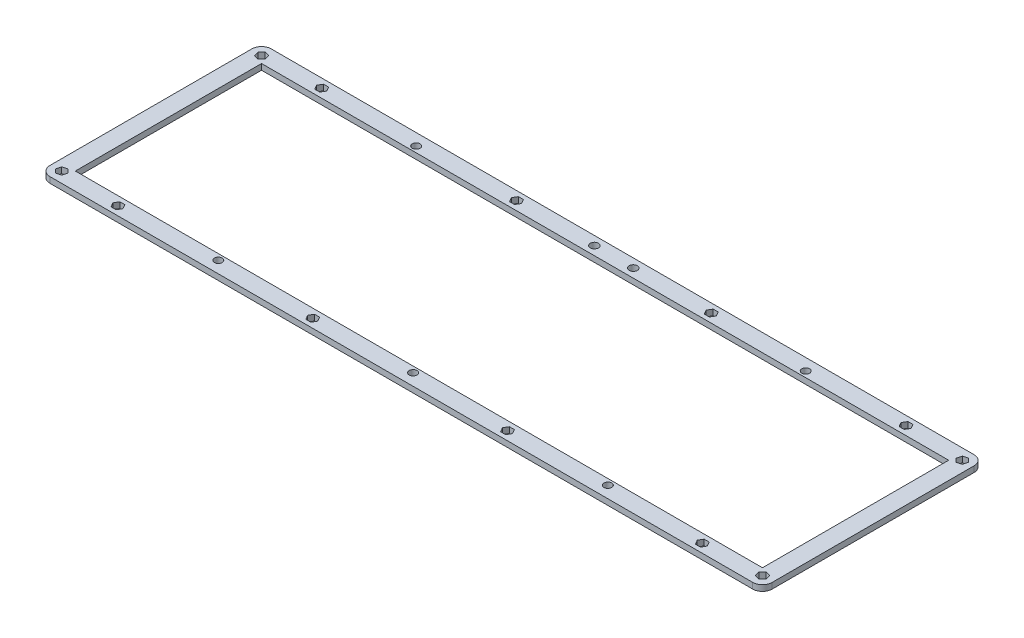
SolidWorks part; units mm, degrees
ref_plane "Front Plane" through (0, 0, 0) normal (0, 0, 1) x (1, 0, 0)
ref_plane "Top Plane" through (0, 0, 0) normal (0, 1, 0) x (1, 0, 0)
ref_plane "Right Plane" through (0, 0, 0) normal (1, 0, 0) x (0, 0, -1)
sketch "Sketch1" plane through (0, 0, 0) normal (0, 1, 0) x (1, 0, 0)
  line L0 (0, 108.6) -> (0, 5)
  line L1 (9, 104.6) -> (9, 9)
  line L2 (365.775, 0) -> (5, 0)
  line L3 (361.775, 9) -> (9, 9)
  line L4 (370.775, 108.6) -> (370.775, 5)
  line L5 (361.775, 104.6) -> (361.775, 9)
  line L6 (365.775, 113.6) -> (5, 113.6)
  line L7 (361.775, 104.6) -> (9, 104.6)
  line L8 (234.0885, 111.35) -> (236.6865, 111.35)
  line L9 (236.6865, 111.35) -> (237.9856, 109.1)
  line L10 (237.9856, 109.1) -> (236.6865, 106.85)
  line L11 (236.6865, 106.85) -> (234.0885, 106.85)
  line L12 (234.0885, 106.85) -> (232.7894, 109.1)
  line L13 (232.7894, 109.1) -> (234.0885, 111.35)
  line L14 (334.0885, 111.35) -> (336.6865, 111.35)
  line L15 (336.6865, 111.35) -> (337.9856, 109.1)
  line L16 (337.9856, 109.1) -> (336.6865, 106.85)
  line L17 (336.6865, 106.85) -> (334.0885, 106.85)
  line L18 (334.0885, 106.85) -> (332.7894, 109.1)
  line L19 (332.7894, 109.1) -> (334.0885, 111.35)
  line L20 (365.9474, 110.6096) -> (367.7846, 108.7724)
  line L21 (367.7846, 108.7724) -> (367.1121, 106.2629)
  line L22 (367.1121, 106.2629) -> (364.6026, 105.5905)
  line L23 (364.6026, 105.5905) -> (362.7655, 107.4276)
  line L24 (362.7655, 107.4276) -> (363.4379, 109.9371)
  line L25 (363.4379, 109.9371) -> (365.9474, 110.6096)
  line L26 (136.6865, 111.35) -> (134.0885, 111.35)
  line L27 (134.0885, 111.35) -> (132.7894, 109.1)
  line L28 (132.7894, 109.1) -> (134.0885, 106.85)
  line L29 (134.0885, 106.85) -> (136.6865, 106.85)
  line L30 (136.6865, 106.85) -> (137.9856, 109.1)
  line L31 (137.9856, 109.1) -> (136.6865, 111.35)
  line L32 (36.6865, 111.35) -> (34.0885, 111.35)
  line L33 (34.0885, 111.35) -> (32.7894, 109.1)
  line L34 (32.7894, 109.1) -> (34.0885, 106.85)
  line L35 (34.0885, 106.85) -> (36.6865, 106.85)
  line L36 (36.6865, 106.85) -> (37.9856, 109.1)
  line L37 (37.9856, 109.1) -> (36.6865, 111.35)
  line L38 (4.8276, 110.6096) -> (2.9905, 108.7724)
  line L39 (2.9905, 108.7724) -> (3.6629, 106.2629)
  line L40 (3.6629, 106.2629) -> (6.1724, 105.5905)
  line L41 (6.1724, 105.5905) -> (8.0096, 107.4276)
  line L42 (8.0096, 107.4276) -> (7.3371, 109.9371)
  line L43 (7.3371, 109.9371) -> (4.8276, 110.6096)
  line L44 (234.0885, 2.25) -> (236.6865, 2.25)
  line L45 (236.6865, 2.25) -> (237.9856, 4.5)
  line L46 (237.9856, 4.5) -> (236.6865, 6.75)
  line L47 (236.6865, 6.75) -> (234.0885, 6.75)
  line L48 (234.0885, 6.75) -> (232.7894, 4.5)
  line L49 (232.7894, 4.5) -> (234.0885, 2.25)
  line L50 (334.0885, 2.25) -> (336.6865, 2.25)
  line L51 (336.6865, 2.25) -> (337.9856, 4.5)
  line L52 (337.9856, 4.5) -> (336.6865, 6.75)
  line L53 (336.6865, 6.75) -> (334.0885, 6.75)
  line L54 (334.0885, 6.75) -> (332.7894, 4.5)
  line L55 (332.7894, 4.5) -> (334.0885, 2.25)
  line L56 (365.9474, 2.9905) -> (367.7846, 4.8276)
  line L57 (367.7846, 4.8276) -> (367.1121, 7.3371)
  line L58 (367.1121, 7.3371) -> (364.6026, 8.0096)
  line L59 (364.6026, 8.0096) -> (362.7655, 6.1724)
  line L60 (362.7655, 6.1724) -> (363.4379, 3.6629)
  line L61 (363.4379, 3.6629) -> (365.9474, 2.9905)
  line L62 (136.6865, 2.25) -> (134.0885, 2.25)
  line L63 (134.0885, 2.25) -> (132.7894, 4.5)
  line L64 (132.7894, 4.5) -> (134.0885, 6.75)
  line L65 (134.0885, 6.75) -> (136.6865, 6.75)
  line L66 (136.6865, 6.75) -> (137.9856, 4.5)
  line L67 (137.9856, 4.5) -> (136.6865, 2.25)
  line L68 (36.6865, 2.25) -> (34.0885, 2.25)
  line L69 (34.0885, 2.25) -> (32.7894, 4.5)
  line L70 (32.7894, 4.5) -> (34.0885, 6.75)
  line L71 (34.0885, 6.75) -> (36.6865, 6.75)
  line L72 (36.6865, 6.75) -> (37.9856, 4.5)
  line L73 (37.9856, 4.5) -> (36.6865, 2.25)
  line L74 (4.8276, 2.9905) -> (2.9905, 4.8276)
  line L75 (2.9905, 4.8276) -> (3.6629, 7.3371)
  line L76 (3.6629, 7.3371) -> (6.1724, 8.0096)
  line L77 (6.1724, 8.0096) -> (8.0096, 6.1724)
  line L78 (8.0096, 6.1724) -> (7.3371, 3.6629)
  line L79 (7.3371, 3.6629) -> (4.8276, 2.9905)
  arc A0 (365.775, 0) -> (370.775, 5) centre (365.775, 5) ccw
  arc A1 (370.775, 108.6) -> (365.775, 113.6) centre (365.775, 108.6) ccw
  arc A2 (0, 5) -> (5, 0) centre (5, 5) ccw
  arc A3 (5, 113.6) -> (0, 108.6) centre (5, 108.6) ccw
  circle A4 centre (85.3875, 107.6) radius 2
  circle A5 centre (285.3875, 107.6) radius 2
  circle A6 centre (85.3875, 6) radius 2
  circle A7 centre (185.3875, 6) radius 2
  circle A8 centre (285.3875, 6) radius 2
  circle A9 centre (175.3875, 109.1) radius 2.1
  circle A10 centre (195.3875, 109.1) radius 2.1
extrude "Boss-Extrude1" add sketch "Sketch1" against normal blind 3
